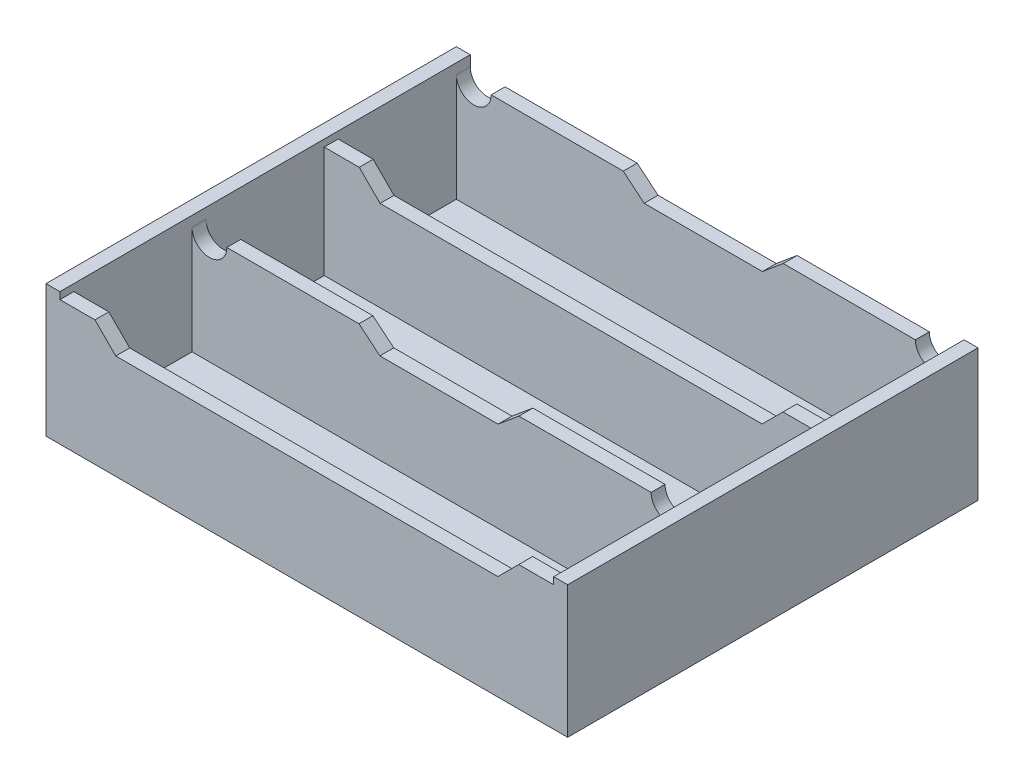
SolidWorks part; units mm, degrees
ref_plane "Front Plane" through (0, 0, 0) normal (0, 0, 1) x (1, 0, 0)
ref_plane "Top Plane" through (0, 0, 0) normal (0, 1, 0) x (1, 0, 0)
ref_plane "Right Plane" through (0, 0, 0) normal (1, 0, 0) x (0, 0, -1)
sketch "Sketch1" plane through (0, 0, 0) normal (0, 1, 0) x (1, 0, 0)
  line L1 (0, 0) -> (75, 0)
  line L2 (0, 0) -> (0, 40)
  line L3 (0, 40) -> (75, 40)
  line L4 (75, 0) -> (75, 40)
  dimension "D1" = 75
  dimension "D2" = 40
extrude "Boss-Extrude1" add sketch "Sketch1" along normal blind 2
sketch "Sketch2" plane through (0, 2, 0) normal (0, 1, 0) x (1, 0, 0)
  line L1 (2, 38) -> (73, 38)
  line L2 (2, 38) -> (2, 21)
  line L3 (2, 21) -> (73, 21)
  line L4 (73, 38) -> (73, 21)
  line L5 (2, 19) -> (73, 19)
  line L6 (2, 19) -> (2, 2)
  line L7 (2, 2) -> (73, 2)
  line L8 (73, 19) -> (73, 2)
  line L9 (0, 40) -> (75, 40)
  line L10 (0, 40) -> (0, 0)
  line L11 (0, 0) -> (75, 0)
  line L12 (75, 40) -> (75, 0)
  point P14 (0, 20)
  dimension "D1" = 2
  dimension "D2" = 2
  dimension "D3" = 2
  dimension "D4" = 2
  dimension "D5" = 2
  dimension "D6" = 1
extrude "Boss-Extrude2" add sketch "Sketch2" along normal blind 17
sketch "Sketch3" plane through (0, 0, 0) normal (0, 0, 1) x (1, 0, 0)
  line L0 (2, 17.5) -> (2, 19)
  line L1 (2, 19) -> (2, 2) construction
  line L2 (2, 19) -> (73, 19)
  line L3 (73, 19) -> (73, 17.5)
  line L4 (73, 19) -> (73, 2) construction
  line L5 (7, 17.5) -> (26, 17.5)
  line L6 (26, 17.5) -> (29, 15)
  line L7 (29, 15) -> (46, 15)
  line L8 (46, 15) -> (49, 17.5)
  line L9 (49, 17.5) -> (68, 17.5)
  arc A0 (2, 17.5) -> (7, 17.5) centre (4.5, 17.5) ccw
  arc A1 (68, 17.5) -> (73, 17.5) centre (70.5, 17.5) ccw
  point P11 (37.5, 15)
  point P21 (37.5, 19)
  dimension "D1" = 5
  dimension "D2" = 17
  dimension "D3" = 3
  dimension "D4" = 1.5
extrude "Cut-Extrude2" cut sketch "Sketch3" against normal blind 17 contours L6 L7 L8 L9 A1 L3 L2 L0 A0 L5
ref_plane "Plane1" through (0, 0, -20) normal (0, 0, 1) x (1, 0, 0)
mirror "Mirror1" about plane through (0, 0, -20) normal (0, 0, 1) of "Cut-Extrude2"
sketch "Sketch4" plane through (0, 0, -19) normal (0, 0, 1) x (1, 0, 0)
  line L0 (2, 18) -> (7.0359, 18)
  line L1 (2, 19) -> (2, 2) construction
  line L2 (7.0359, 18) -> (10.0359, 15)
  line L3 (10.0359, 15) -> (64.9641, 15)
  line L4 (64.9641, 15) -> (67.9641, 18)
  line L5 (67.9641, 18) -> (73, 18)
  line L6 (73, 19) -> (73, 2) construction
  line L7 (46, 15) -> (29, 15) construction
  line L9 (73, 19) -> (2, 19) construction
  line L10 (2, 18) -> (2, 19)
  line L11 (2, 19) -> (73, 19)
  line L12 (73, 19) -> (73, 18)
  dimension "D1" = 1
  dimension "D2" = 3
extrude "Cut-Extrude3" cut sketch "Sketch4" against normal up to next contours L2 L3 L4 L5 L12 L11 L10 L0
sketch "Sketch5" plane through (0, 2, 0) normal (0, 1, 0) x (1, 0, 0)
  line L0 (2, 38) -> (2, 21) construction
  line L1 (2, 19) -> (2, 2) construction
  line L2 (73, 38) -> (2, 38) construction
  circle A0 centre (37.5, 29.5) radius 1.6
  circle A1 centre (37.5, 10.5) radius 1.6
  point P4 (2, 29.5)
  point P5 (2, 10.5)
  point P8 (37.5, 38)
  dimension "D1" = 3.2
extrude "Cut-Extrude4" cut sketch "Sketch5" against normal up to next
ref_plane "Plane2" through (0, 0, -1) normal (0, 0, 1) x (1, 0, 0)
mirror "Mirror2" about plane through (0, 0, -1) normal (0, 0, 1) of "Cut-Extrude4", "Cut-Extrude3", "Mirror1", "Cut-Extrude2", "Boss-Extrude2", "Boss-Extrude1"
sketch "Sketch7" plane through (0, 0, 38) normal (0, 0, 1) x (1, 0, 0)
  line L1 (-2.3224, 21.7235) -> (77.9375, 21.7235)
  line L2 (-2.3224, 21.7235) -> (-2.3224, -1.6472)
  line L3 (-2.3224, -1.6472) -> (77.9375, -1.6472)
  line L4 (77.9375, 21.7235) -> (77.9375, -1.6472)
extrude "Cut-Extrude5" cut sketch "Sketch7" against normal up to surface (19 mm away) up to face at (37.5, 13.25, 19)
